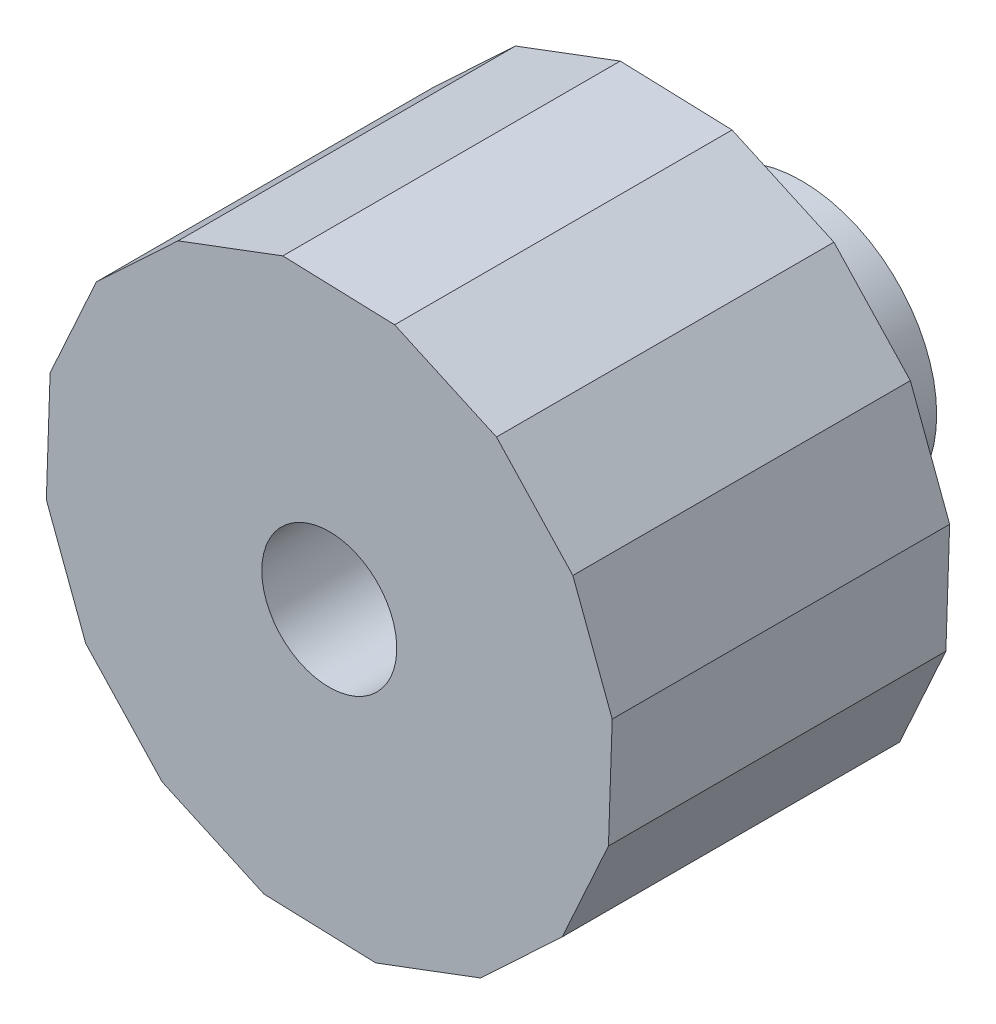
SolidWorks part; units mm, degrees
material "Настроенная пользователем пластмасса"
ref_plane "Спереди" through (0, 0, 0) normal (0, 0, 1) x (1, 0, 0)
ref_plane "Сверху" through (0, 0, 0) normal (0, 1, 0) x (1, 0, 0)
ref_plane "Справа" through (0, 0, 0) normal (1, 0, 0) x (0, 0, -1)
sketch "Эскиз1" plane through (0, 0, 0) normal (0, 0, 1) x (1, 0, 0)
  line L1 (10.8286, 6.7212) -> (7.4322, 10.3535)
  line L2 (7.4322, 10.3535) -> (2.9044, 12.4095)
  line L3 (2.9044, 12.4095) -> (-2.0656, 12.5764)
  line L4 (-2.0656, 12.5764) -> (-6.7212, 10.8286)
  line L5 (-6.7212, 10.8286) -> (-10.3535, 7.4322)
  line L6 (-10.3535, 7.4322) -> (-12.4095, 2.9044)
  line L7 (-12.4095, 2.9044) -> (-12.5764, -2.0656)
  line L8 (-12.5764, -2.0656) -> (-10.8286, -6.7212)
  line L9 (-10.8286, -6.7212) -> (-7.4322, -10.3535)
  line L10 (-7.4322, -10.3535) -> (-2.9044, -12.4095)
  line L11 (-2.9044, -12.4095) -> (2.0656, -12.5764)
  line L12 (2.0656, -12.5764) -> (6.7212, -10.8286)
  line L13 (6.7212, -10.8286) -> (10.3535, -7.4322)
  line L14 (10.3535, -7.4322) -> (12.4095, -2.9044)
  line L15 (12.4095, -2.9044) -> (12.5764, 2.0656)
  line L16 (12.5764, 2.0656) -> (10.8286, 6.7212)
  circle A0 centre (0, 0) radius 12.5 construction
extrude "Бобышка-Вытянуть1" add sketch "Эскиз1" along normal blind 15
sketch "Эскиз2" plane through (0, 0, 0) normal (0, 0, -1) x (-1, 0, 0)
  circle A0 centre (0, 0) radius 6
extrude "Бобышка-Вытянуть2" add sketch "Эскиз2" along normal blind 6
sketch "Эскиз3" plane through (0, 0, -6) normal (0, 0, -1) x (-1, 0, 0)
  circle A0 centre (0, 0) radius 3
extrude "Вырез-Вытянуть1" cut sketch "Эскиз3" against normal through all
